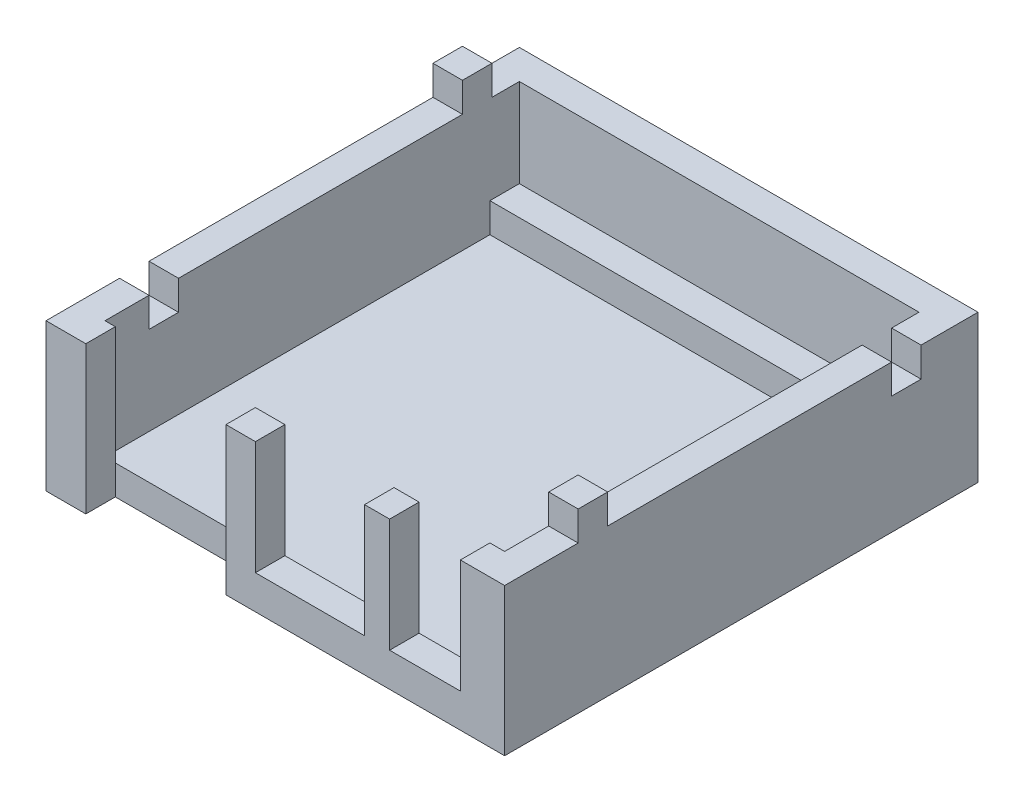
SolidWorks part; units mm, degrees
ref_plane "Front Plane" through (0, 0, 0) normal (0, 0, 1) x (1, 0, 0)
ref_plane "Top Plane" through (0, 0, 0) normal (0, 1, 0) x (1, 0, 0)
ref_plane "Right Plane" through (0, 0, 0) normal (1, 0, 0) x (0, 0, -1)
sketch "Sketch3" plane through (0, 0, 0) normal (0, 1, 0) x (1, 0, 0)
  line L1 (0, 0) -> (31.1, 0)
  line L2 (0, 0) -> (0, -32.1)
  line L3 (0, -32.1) -> (31.1, -32.1)
  line L4 (31.1, 0) -> (31.1, -32.1)
  dimension "D1" = 32.1
  dimension "D2" = 31.1
extrude "Shell" add sketch "Sketch3" along normal blind 10
sketch "Sketch4" plane through (0, 10, 0) normal (0, 1, 0) x (1, 0, 0)
  line L0 (31.1, 0) -> (0, 0) construction
  line L1 (2, -4) -> (29.1, -4)
  line L2 (2, -4) -> (2, -30.1)
  line L3 (2, -30.1) -> (29.1, -30.1)
  line L4 (29.1, -4) -> (29.1, -30.1)
  line L5 (31.1, -32.1) -> (31.1, 0) construction
  line L6 (0, 0) -> (0, -32.1) construction
  line L7 (0, -32.1) -> (31.1, -32.1) construction
  dimension "D1" = 4
  dimension "D2" = 2
  dimension "D3" = 2
  dimension "D4" = 2
extrude "Main Cavity" cut sketch "Sketch4" against normal offset from surface (8 mm away) 2 up to face at (15.55, 0, 16.05)
sketch "Sketch5" plane through (0, 10, 0) normal (0, 1, 0) x (1, 0, 0)
  line L0 (29.1, -30.1) -> (29.1, -4) construction
  line L1 (2, -4) -> (29.1, -4)
  line L2 (2, -4) -> (2, -2)
  line L3 (2, -2) -> (29.1, -2)
  line L4 (29.1, -4) -> (29.1, -2)
  dimension "D1" = 2
extrude "Support Shelf" cut sketch "Sketch5" against normal offset from surface (6 mm away) 2 up to face at (15.55, 2, 17.05)
sketch "Sketch6" plane through (0, 0, 32.1) normal (0, 0, 1) x (1, 0, 0)
  line L0 (0, 0) -> (31.1, 0) construction
  line L2 (28.1, 2.3) -> (28.1, 10)
  line L3 (28.1, 10) -> (23.3, 10)
  line L5 (0, 10) -> (31.1, 10) construction
  line L7 (21.6, 2.3) -> (21.6, 10)
  line L8 (21.6, 10) -> (14.2, 10)
  line L9 (14.2, 2.3) -> (14.2, 10)
  line L10 (12.2, 0) -> (2.7, 0)
  line L11 (12.2, 0) -> (12.2, 10)
  line L12 (12.2, 10) -> (2.7, 10)
  line L13 (2.7, 0) -> (2.7, 10)
  line L14 (31.1, 10) -> (31.1, 0) construction
  line L15 (14.2, 2.3) -> (21.6, 2.3)
  line L16 (23.3, 10) -> (23.3, 2.3)
  line L17 (23.3, 2.3) -> (28.1, 2.3)
  dimension "D1" = 3
  dimension "D2" = 4.8
  dimension "D3" = 7.4
  dimension "D4" = 1.7
  dimension "D5" = 2
  dimension "D6" = 9.5
  dimension "D7" = 2.3
  dimension "D8" = 2.3
extrude "Terminal Input" cut sketch "Sketch6" against normal up to surface (2 mm away) up to face at (15.55, 6, 30.1)
sketch "Sketch7" plane through (0, 10, 0) normal (0, 1, 0) x (1, 0, 0)
  line L0 (31.1, -32.1) -> (31.1, 0) construction
  line L1 (29.1, -25.113) -> (31.1, -25.113)
  line L2 (29.1, -25.113) -> (29.1, -27.113)
  line L3 (29.1, -27.113) -> (31.1, -27.113)
  line L4 (31.1, -25.113) -> (31.1, -27.113)
  line L5 (0, -3.8597) -> (2, -3.8597)
  line L6 (0, -3.8597) -> (0, -5.8597)
  line L7 (0, -5.8597) -> (2, -5.8597)
  line L8 (2, -3.8597) -> (2, -5.8597)
  line L9 (29.1, -30.1) -> (29.1, -2) construction
  line L10 (2, -2) -> (2, -30.1) construction
  line L11 (0, 0) -> (0, -32.1) construction
  dimension "D1" = 2
  dimension "D2" = 2
extrude "Male Tabs" add sketch "Sketch7" along normal blind 2
sketch "Sketch8" plane through (0, 10, 0) normal (0, 1, 0) x (1, 0, 0)
  line L0 (2, -3.8597) -> (0, -3.8597) construction
  line L1 (29.1, -3.8597) -> (31.1, -3.8597)
  line L2 (29.1, -3.8597) -> (29.1, -5.8597)
  line L3 (29.1, -5.8597) -> (31.1, -5.8597)
  line L4 (31.1, -3.8597) -> (31.1, -5.8597)
  line L5 (0, -25.113) -> (2, -25.113)
  line L6 (0, -25.113) -> (0, -27.113)
  line L7 (0, -27.113) -> (2, -27.113)
  line L8 (2, -25.113) -> (2, -27.113)
  line L9 (31.1, -25.113) -> (31.1, 0) construction
  line L11 (29.1, -4) -> (29.1, -30.1) construction
  line L12 (0, -5.8597) -> (0, -32.1) construction
  line L13 (2, -5.8597) -> (2, -30.1) construction
  line L14 (29.1, -27.113) -> (31.1, -27.113) construction
  point P8 (30.1, -3.8597)
  dimension "D1" = 2
  dimension "D2" = 2
extrude "Cut-Extrude4" cut sketch "Sketch8" against normal blind 2
